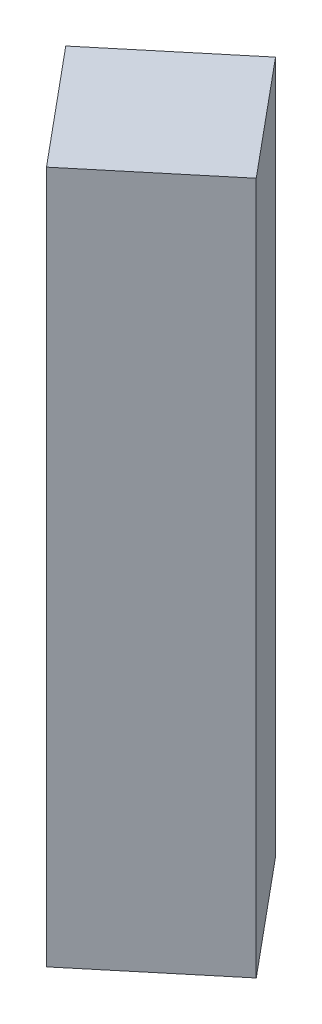
SolidWorks part; units mm, degrees
ref_plane "Front" through (0, 0, 0) normal (0, 0, 1) x (1, 0, 0)
ref_plane "Top" through (0, 0, 0) normal (0, 1, 0) x (1, 0, 0)
ref_plane "Right" through (0, 0, 0) normal (1, 0, 0) x (0, 0, -1)
sketch "Esquisse1" plane through (0, 0, 0) normal (0, 1, 0) x (1, 0, 0)
  line L0 (0, -50) -> (0, 50) construction
  line L1 (-6.4701, -70.414) -> (70.414, -6.4701)
  line L2 (-6.4701, -70.414) -> (-70.414, 6.4701)
  line L3 (-70.414, 6.4701) -> (6.4701, 70.414)
  line L4 (70.414, -6.4701) -> (6.4701, 70.414)
  line L5 (-6.4701, -70.414) -> (6.4701, 70.414) construction
  line L6 (-70.414, 6.4701) -> (70.414, -6.4701) construction
  point P0 (0, 0)
  dimension "D1" = 100
  dimension "D2" = 5.25
extrude "Boss.-Extru.1" add sketch "Esquisse1" along normal blind 465
